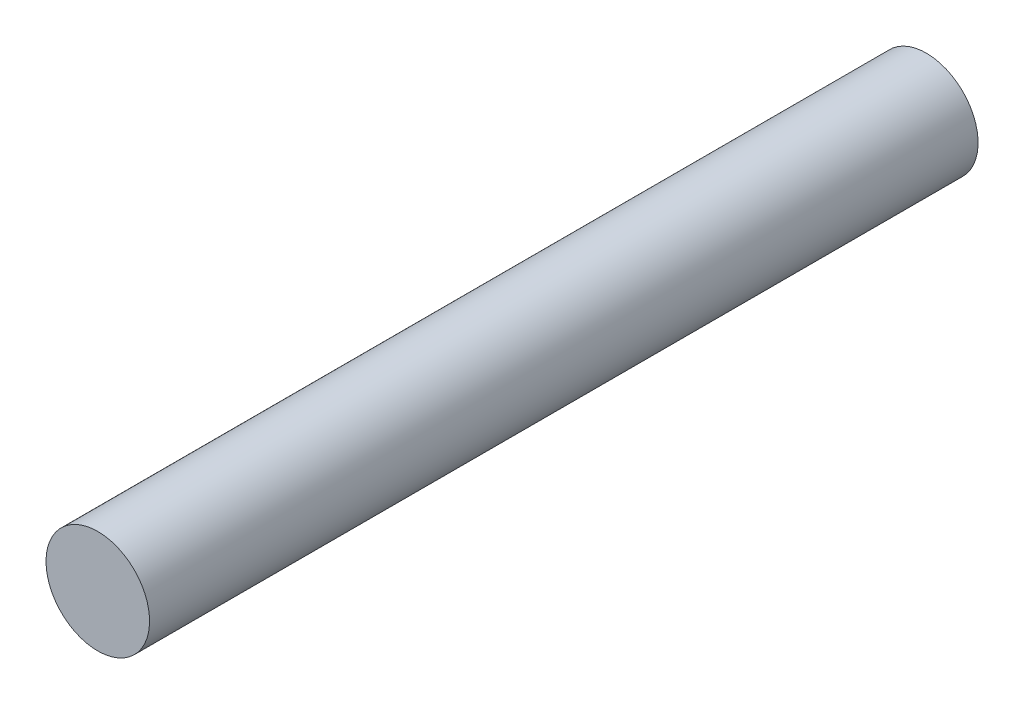
SolidWorks part; units mm, degrees
material "Plain Carbon Steel"
ref_plane "Front" through (0, 0, 0) normal (0, 0, 1) x (1, 0, 0)
ref_plane "Top" through (0, 0, 0) normal (0, 1, 0) x (1, 0, 0)
ref_plane "Right" through (0, 0, 0) normal (1, 0, 0) x (0, 0, -1)
sketch "Sketch1" plane through (0, 0, 0) normal (0, 0, 1) x (1, 0, 0)
  circle A0 centre (0, 0) radius 4.7625
  dimension "D1" = 9.525
extrude "Boss-Extrude1" add sketch "Sketch1" along normal mid plane 76.2
cosmetic thread "Cosmetic Thread1" parameters "D2"=7.6327
